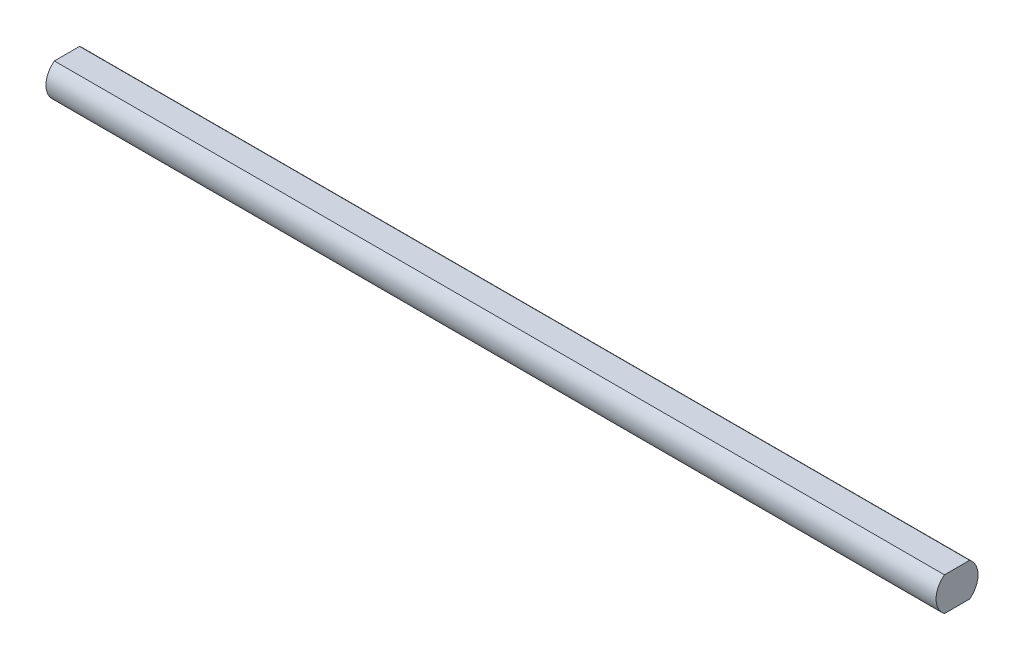
SolidWorks part; units mm, degrees
ref_plane "Front Plane" through (0, 0, 0) normal (0, 0, 1) x (1, 0, 0)
ref_plane "Top Plane" through (0, 0, 0) normal (0, 1, 0) x (1, 0, 0)
ref_plane "Right Plane" through (0, 0, 0) normal (1, 0, 0) x (0, 0, -1)
sketch "Sketch1" plane through (0, 0, 0) normal (0, 0, 1) x (1, 0, 0)
  line L0 (-106, 0) -> (106, 0)
  line L1 (106, 0) -> (106, -5)
  line L2 (106, -5) -> (-106, -5)
  line L3 (-106, -5) -> (-106, 0)
  dimension "D1" = 5
  dimension "D2" = 212
revolve "Revolve1" add sketch "Sketch1" angle 360 about L0
sketch "Sketch2" plane through (106, 0, 0) normal (1, 0, 0) x (0, 0, -1)
  line L0 (-3, 4) -> (3, 4)
  line L1 (0, 0) -> (2.6931, 0) construction
  line L2 (-3, -4) -> (3, -4)
  arc A0 (-3, 4) -> (3, 4) centre (0, 0) cw
  circle A1 centre (0, 0) radius 5 construction
  arc A2 (-3, -4) -> (3, -4) centre (0, 0) ccw
  point P3 (0, 5)
  circle M4 centre (0, 0) radius 5
  dimension "D1" = 1
extrude "Cut-Extrude1" cut sketch "Sketch2" against normal up to surface (212 mm away) contours L2 M4 | A0 L0 up to face at (-106, 0, 5)
